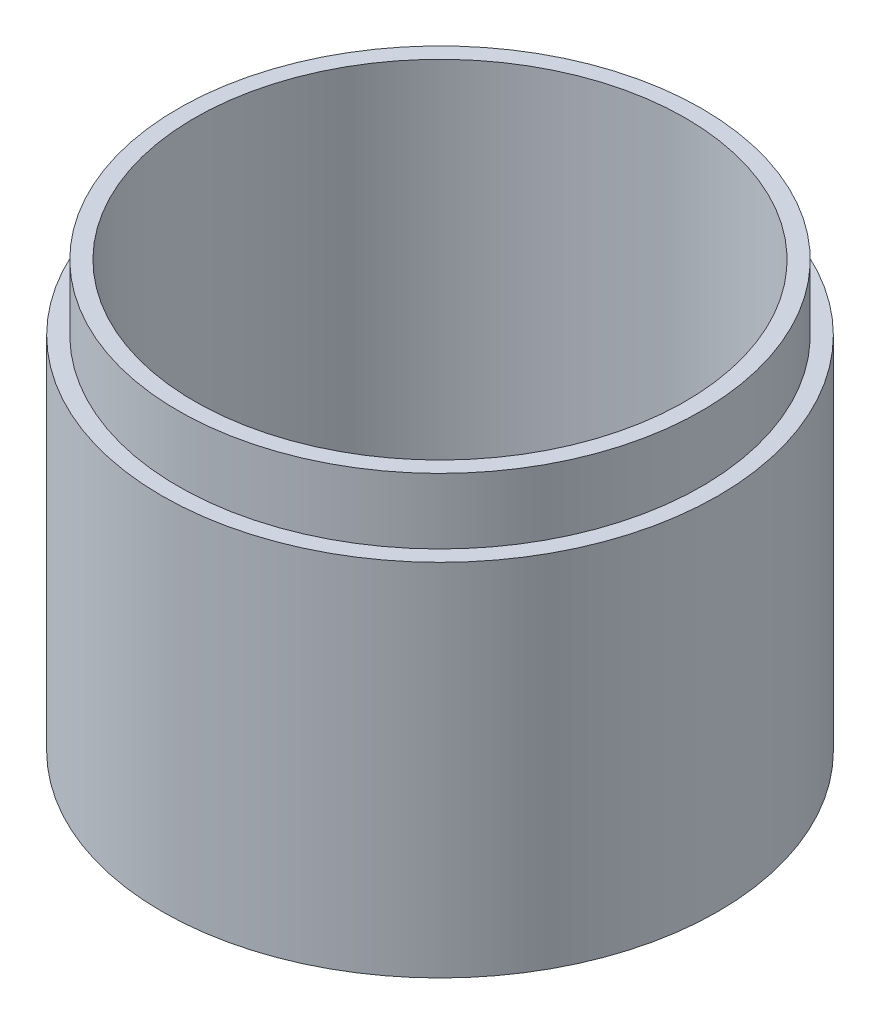
SolidWorks part; units mm, degrees
material "Алюминиевая бронза"
ref_plane "Спереди" through (0, 0, 0) normal (0, 0, 1) x (1, 0, 0)
ref_plane "Сверху" through (0, 0, 0) normal (0, 1, 0) x (1, 0, 0)
ref_plane "Справа" through (0, 0, 0) normal (1, 0, 0) x (0, 0, -1)
sketch "Эскиз1" plane through (0, 0, 0) normal (0, 0, 1) x (1, 0, 0)
  line L0 (0, 0) -> (0, 35.4212) construction
  line L1 (-15, 0) -> (-15, 26)
  line L2 (-15, 26) -> (-16, 26)
  line L3 (-16, 26) -> (-16, 22)
  line L4 (-16, 22) -> (-17, 22)
  line L5 (-17, 22) -> (-17, 0)
  line L6 (-17, 0) -> (-15, 0)
  dimension "D1" = 4
  dimension "D2" = 26
  dimension "D3" = 30
  dimension "D4" = 34
  dimension "D5" = 1
revolve "Повернуть1" add sketch "Эскиз1" angle 360 about L0
